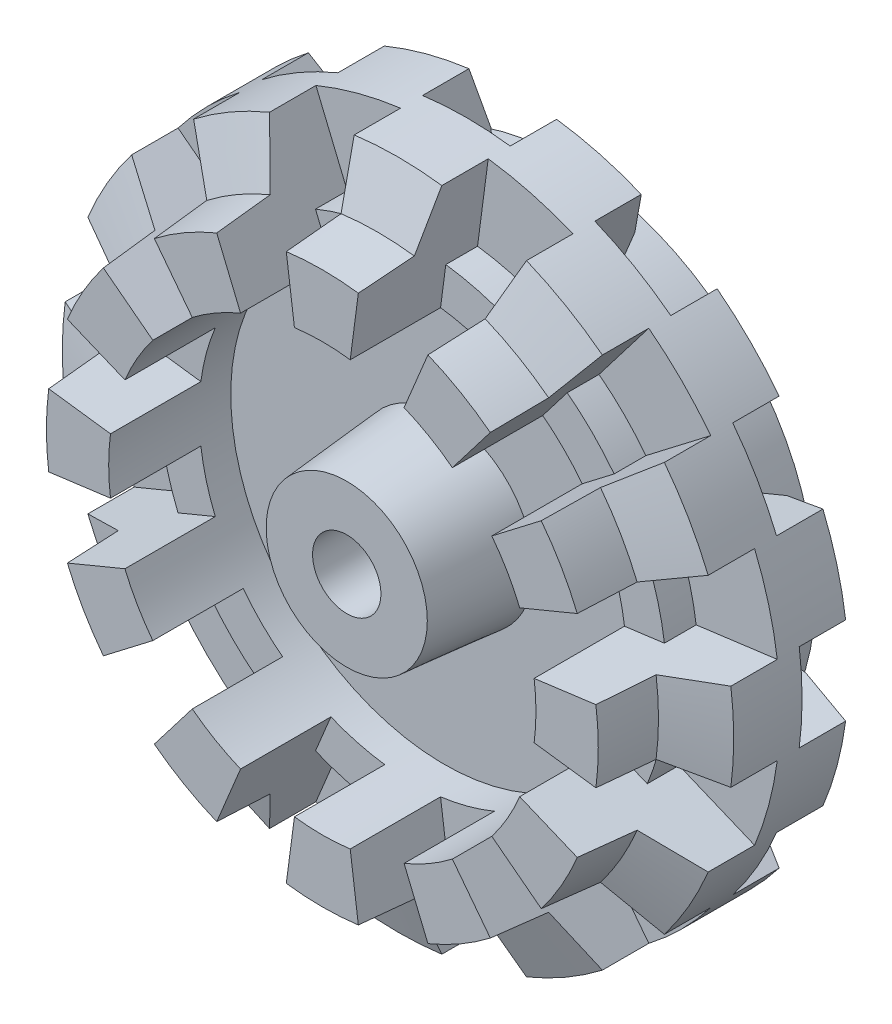
SolidWorks part; units mm, degrees
material "ABS"
ref_plane "Front Plane" through (0, 0, 0) normal (0, 0, 1) x (1, 0, 0)
ref_plane "Top Plane" through (0, 0, 0) normal (0, 1, 0) x (1, 0, 0)
ref_plane "Right Plane" through (0, 0, 0) normal (1, 0, 0) x (0, 0, -1)
sketch "Sketch1" plane through (0, 0, 0) normal (0, 0, 1) x (1, 0, 0)
  circle A0 centre (0, 0) radius 17.4625
  dimension "D1" = 34.925
extrude "Boss-Extrude1" add sketch "Sketch1" along normal blind 1.143
sketch "Sketch2" plane through (0, 0, 1.143) normal (0, 0, 1) x (1, 0, 0)
  line L0 (0, 0) -> (0, 18.8753)
  line L1 (-2.485, 18.8753) -> (2.485, 18.8753)
  line L2 (2.485, 18.8753) -> (0, 0)
  line L3 (-2.485, 18.8753) -> (0, 0)
  line L4 (11.5897, 15.104) -> (0, 0)
  line L5 (7.2856, 17.589) -> (0, 0)
  line L6 (17.589, 7.2856) -> (0, 0)
  line L7 (15.104, 11.5897) -> (0, 0)
  line L8 (18.8753, -2.485) -> (0, 0)
  line L9 (18.8753, 2.485) -> (0, 0)
  line L10 (15.104, -11.5897) -> (0, 0)
  line L11 (17.589, -7.2856) -> (0, 0)
  line L12 (7.2856, -17.589) -> (0, 0)
  line L13 (11.5897, -15.104) -> (0, 0)
  line L14 (-2.485, -18.8753) -> (0, 0)
  line L15 (2.485, -18.8753) -> (0, 0)
  line L16 (-11.5897, -15.104) -> (0, 0)
  line L17 (-7.2856, -17.589) -> (0, 0)
  line L18 (-17.589, -7.2856) -> (0, 0)
  line L19 (-15.104, -11.5897) -> (0, 0)
  line L20 (-18.8753, 2.485) -> (0, 0)
  line L21 (-18.8753, -2.485) -> (0, 0)
  line L22 (-15.104, 11.5897) -> (0, 0)
  line L23 (-17.589, 7.2856) -> (0, 0)
  line L24 (-7.2856, 17.589) -> (0, 0)
  line L25 (-11.5897, 15.104) -> (0, 0)
  arc A0 (-2.2793, 17.3131) -> (2.2793, 17.3131) centre (0, 0) cw
  circle A1 centre (0, 0) radius 17.4625 construction
  arc A2 (6.6826, 16.1332) -> (10.6305, 13.8539) centre (0, 0) cw
  arc A3 (13.8539, 10.6305) -> (16.1332, 6.6826) centre (0, 0) cw
  arc A4 (17.3131, 2.2793) -> (17.3131, -2.2793) centre (0, 0) cw
  arc A5 (16.1332, -6.6826) -> (13.8539, -10.6305) centre (0, 0) cw
  arc A6 (10.6305, -13.8539) -> (6.6826, -16.1332) centre (0, 0) cw
  arc A7 (2.2793, -17.3131) -> (-2.2793, -17.3131) centre (0, 0) cw
  arc A8 (-6.6826, -16.1332) -> (-10.6305, -13.8539) centre (0, 0) cw
  arc A9 (-13.8539, -10.6305) -> (-16.1332, -6.6826) centre (0, 0) cw
  arc A10 (-17.3131, -2.2793) -> (-17.3131, 2.2793) centre (0, 0) cw
  arc A11 (-16.1332, 6.6826) -> (-13.8539, 10.6305) centre (0, 0) cw
  arc A12 (-10.6305, 13.8539) -> (-6.6826, 16.1332) centre (0, 0) cw
  circle A13 centre (0, 0) radius 11.1125
  dimension "D3" = 22.225
  dimension "D1" = 7.5
  dimension "D2" = 12
extrude "Boss-Extrude2" add sketch "Sketch2" along normal blind 6.35 contours A13 L0 L3 | A13 L2 L0 | A13 L4 L0 L5 | A13 L6 L0 L7 | A13 L8 L0 L9 | A13 L10 L0 L11 | A13 L12 L0 L13 | A13 L14 L0 L15 | A13 L16 L0 L17 | A13 L18 L0 L19 | A13 L20 L0 L21 | A13 L22 L0 L23 | A13 L24 L0 L25
sketch "Sketch4" plane through (0, 0, 1.143) normal (0, 0, 1) x (1, 0, 0)
  circle A0 centre (0, 0) radius 4.6355
  dimension "D1" = 9.271
extrude "Boss-Extrude3" add sketch "Sketch4" along normal blind 5.08
draft "Draft1" type of draft neutral plane draft angle 5 faces to draft 1 face at (4.6355, 0, 6.223) neutral plane through (0, 0, 1.143) neutral plane normal (0, 0, 1) parameters "D1"=5
sketch "Sketch5" plane through (0, 0, 0) normal (0, 0, -1) x (-1, 0, 0)
  circle A0 centre (0, 0) radius 4.064
  dimension "D1" = 8.128
extrude "Boss-Extrude4" add sketch "Sketch5" along normal blind 1.27
sketch "Sketch6" plane through (0, 0, 0) normal (0, 0, -1) x (-1, 0, 0)
  line L0 (0, 0) -> (2.42, 18.3817)
  line L1 (2.42, 18.3817) -> (-2.42, 18.3817)
  line L2 (0, 18.3817) -> (0, 0)
  line L3 (0, 0) -> (-2.42, 18.3817)
  line L4 (0, 0) -> (11.2866, 14.709)
  line L5 (0, 0) -> (7.0951, 17.129)
  line L6 (0, 0) -> (17.129, 7.0951)
  line L7 (0, 0) -> (14.709, 11.2866)
  line L8 (0, 0) -> (18.3817, -2.42)
  line L9 (0, 0) -> (18.3817, 2.42)
  line L10 (0, 0) -> (14.709, -11.2866)
  line L11 (0, 0) -> (17.129, -7.0951)
  line L12 (0, 0) -> (7.0951, -17.129)
  line L13 (0, 0) -> (11.2866, -14.709)
  line L14 (0, 0) -> (-2.42, -18.3817)
  line L15 (0, 0) -> (2.42, -18.3817)
  line L16 (0, 0) -> (-11.2866, -14.709)
  line L17 (0, 0) -> (-7.0951, -17.129)
  line L18 (0, 0) -> (-17.129, -7.0951)
  line L19 (0, 0) -> (-14.709, -11.2866)
  line L20 (0, 0) -> (-18.3817, 2.42)
  line L21 (0, 0) -> (-18.3817, -2.42)
  line L22 (0, 0) -> (-14.709, 11.2866)
  line L23 (0, 0) -> (-17.129, 7.0951)
  line L24 (0, 0) -> (-7.0951, 17.129)
  line L25 (0, 0) -> (-11.2866, 14.709)
  arc A0 (-2.2793, 17.3131) -> (2.2793, 17.3131) centre (0, 0) ccw
  arc A1 (6.6826, 16.1332) -> (10.6305, 13.8539) centre (0, 0) ccw
  arc A2 (13.8539, 10.6305) -> (16.1332, 6.6826) centre (0, 0) ccw
  arc A3 (17.3131, 2.2793) -> (17.3131, -2.2793) centre (0, 0) ccw
  arc A4 (16.1332, -6.6826) -> (13.8539, -10.6305) centre (0, 0) ccw
  arc A5 (10.6305, -13.8539) -> (6.6826, -16.1332) centre (0, 0) ccw
  arc A6 (2.2793, -17.3131) -> (-2.2793, -17.3131) centre (0, 0) ccw
  arc A7 (-6.6826, -16.1332) -> (-10.6305, -13.8539) centre (0, 0) ccw
  arc A8 (-13.8539, -10.6305) -> (-16.1332, -6.6826) centre (0, 0) ccw
  arc A9 (-17.3131, -2.2793) -> (-17.3131, 2.2793) centre (0, 0) ccw
  arc A10 (-16.1332, 6.6826) -> (-13.8539, 10.6305) centre (0, 0) ccw
  arc A11 (-10.6305, 13.8539) -> (-6.6826, 16.1332) centre (0, 0) ccw
  circle A12 centre (0, 0) radius 10.414
  circle M1 centre (0, 0) radius 17.4625
  dimension "D3" = 20.828
  dimension "D1" = 7.5
  dimension "D2" = 12
extrude "Boss-Extrude5" add sketch "Sketch6" along normal blind 3.175 contours A12 L3 L24 M1 | A12 L5 L0 M1 | A12 L7 L4 M1 | A12 L9 L6 M1 | A12 L11 L8 M1 | A12 L13 L10 M1 | A12 L15 L12 M1 | A12 L17 L14 M1 | A12 L19 L16 M1 | A12 L21 L18 M1 | A12 L23 L20 M1 | A12 L25 L22 M1
sketch "Sketch7" plane through (0, 0, 0) normal (0, 0, -1) x (-1, 0, 0)
  circle A0 centre (0, 0) radius 10.414
  circle A1 centre (0, 0) radius 13.081
  dimension "D1" = 26.162
extrude "Boss-Extrude6" add sketch "Sketch7" along normal blind 5.08
sketch "Sketch9" plane through (0, 0, 0) normal (0, 1, 0) x (1, 0, 0)
  line L0 (0, 0) -> (17.4625, 0)
  line L1 (17.4625, 0) -> (17.4625, 2.413)
  line L2 (17.4625, 2.413) -> (14.605, 3.175)
  line L3 (14.605, 3.175) -> (13.081, 3.175)
  line L4 (13.081, 0) -> (13.081, 5.08) construction
  line L5 (13.081, 3.175) -> (13.081, 0)
  line L6 (17.4625, 2.413) -> (17.4625, 3.175)
  line L7 (17.4625, 3.175) -> (14.605, 3.175)
  line L8 (0, 0) -> (0, -1.143)
  line L9 (-1.4505, -1.143) -> (1.4505, -1.143) construction
  line L10 (0, -1.143) -> (17.4625, -1.143)
  line L11 (17.4625, -7.493) -> (17.4625, 0) construction
  line L12 (17.4625, -1.143) -> (17.4625, -3.556)
  line L13 (13.335, -4.6121) -> (14.605, -4.6121)
  line L14 (17.4625, -3.556) -> (14.605, -4.6121)
  line L15 (13.335, -4.6121) -> (13.335, -1.143)
  line L16 (14.605, 3.175) -> (14.605, -4.6121)
  line L17 (14.605, -4.6121) -> (17.4625, -4.6121)
  line L18 (17.4625, -4.6121) -> (17.4625, -3.556)
  line L19 (13.335, -4.6121) -> (13.335, -7.493)
  line L20 (13.8539, -7.493) -> (8.8161, -7.493) construction
  line L21 (13.335, -7.493) -> (14.3529, -7.493)
  line L22 (13.8539, -7.493) -> (16.1332, -7.493) construction
  line L23 (14.3529, -7.493) -> (14.605, -4.6121)
  line L24 (17.4625, -4.6121) -> (17.4625, -7.493)
  line L25 (17.3131, -7.493) -> (17.4625, -7.493) construction
  line L26 (17.4625, -7.493) -> (14.3529, -7.493)
  dimension "D1" = 2.413
  dimension "D2" = 1.524
  dimension "D3" = 17.4625
  dimension "D4" = 3.175
  dimension "D5" = 13.335
  dimension "D6" = 2.413
  dimension "D7" = 85
sketch3d "3DSketch1"
  line L0 (0, 0, 0) -> (0, 0, -2.54) construction
revolve "Cut-Revolve1" cut sketch "Sketch9" angle 360 about L0
sketch "Sketch10" plane through (0, 0, 6.223) normal (0, 0, 1) x (1, 0, 0)
  circle A0 centre (0, 0) radius 1.778
  dimension "D1" = 3.556
extrude "Cut-Extrude1" cut sketch "Sketch10" against normal through all
sketch "Sketch11" plane through (0, 0, 1.143) normal (0, 0, 1) x (1, 0, 0)
  circle A0 centre (0, 0) radius 11.1125
  circle A1 centre (0, 0) radius 13.208
  dimension "D1" = 26.416
extrude "Boss-Extrude7" add sketch "Sketch11" along normal blind 1.651
